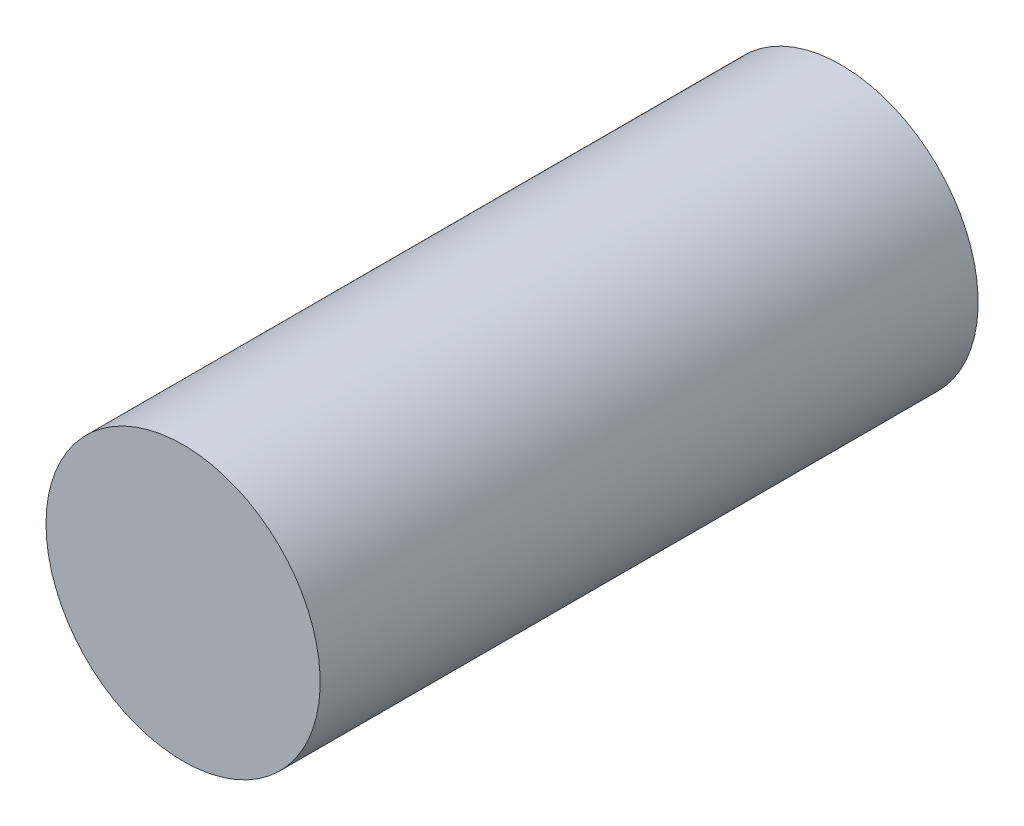
SolidWorks part; units mm, degrees
material "1060 Alloy"
ref_plane "Front Plane" through (0, 0, 0) normal (0, 0, 1) x (1, 0, 0)
ref_plane "Top Plane" through (0, 0, 0) normal (0, 1, 0) x (1, 0, 0)
ref_plane "Right Plane" through (0, 0, 0) normal (1, 0, 0) x (0, 0, -1)
sketch "Sketch1" plane through (0, 0, 0) normal (0, 0, 1) x (1, 0, 0)
  circle A0 centre (0, 0) radius 7.9375
extrude "Boss-Extrude1" add sketch "Sketch1" along normal blind 38.1
